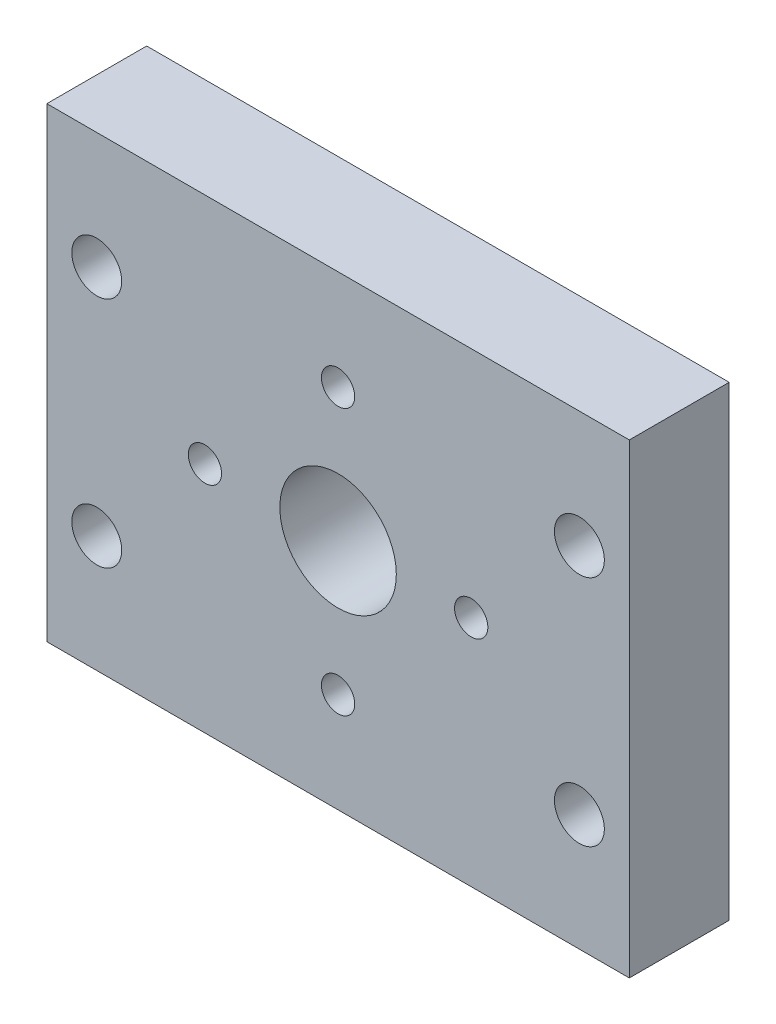
SolidWorks part; units mm, degrees
ref_plane "Plan de face" through (0, 0, 0) normal (0, 0, 1) x (1, 0, 0)
ref_plane "Plan de dessus" through (0, 0, 0) normal (0, 1, 0) x (1, 0, 0)
ref_plane "Plan de droite" through (0, 0, 0) normal (1, 0, 0) x (0, 0, -1)
sketch "Esquisse1" plane through (0, 0, 0) normal (0, 0, 1) x (1, 0, 0)
  line L0 (0, 0) -> (44.4207, 0) construction
  line L1 (17.5, -14) -> (-17.5, -14)
  line L2 (17.5, -14) -> (17.5, 14)
  line L3 (17.5, 14) -> (-17.5, 14)
  line L4 (-17.5, -14) -> (-17.5, 14)
  line L5 (17.5, -14) -> (-17.5, 14) construction
  line L6 (17.5, 14) -> (-17.5, -14) construction
  line L7 (0, 0) -> (0, -37.0394) construction
  line L8 (-11.5, 15) -> (-11.5, -24.3494) construction
  line L10 (-17.5, 14) -> (-11.5, 0) construction
  circle A0 centre (0, 0) radius 3.5
  circle A1 centre (0, 8) radius 1
  circle A2 centre (8, 0) radius 1
  circle A3 centre (0, -8) radius 1
  circle A4 centre (-8, 0) radius 1
  circle A5 centre (-14.5, 7) radius 1.5
  circle A6 centre (-14.5, -7) radius 1.5
  circle A7 centre (14.5, -7) radius 1.5
  circle A8 centre (14.5, 7) radius 1.5
  point P0 (0, 0)
  dimension "D1" = 7
  dimension "D2" = 2
  dimension "D3" = 2
  dimension "D4" = 2
  dimension "D5" = 2
  dimension "D7" = 8
  dimension "D12" = 3
  dimension "D6" = 8
  dimension "D8" = 8
  dimension "D9" = 8
  dimension "D10" = 35
  dimension "D11" = 28
  dimension "D15" = 3
extrude "Boss.-Extru.1" add sketch "Esquisse1" along normal blind 6 contours L4 L3 L2 L1 | A0 | A1 | A4 | A3 | A2 | A5 | A7 | A6 | A8
sketch "Esquisse2" plane through (0, 0, 6) normal (0, 0, 1) x (1, 0, 0)
  line L0 (17.5, 14) -> (-17.5, 14) construction
  line L1 (17.5, -14) -> (11.5, -14)
  line L2 (17.5, -14) -> (17.5, 14)
  line L3 (17.5, 14) -> (11.5, 14)
  line L4 (11.5, -14) -> (11.5, 14)
sketch "Esquisse5" plane through (0, 0, 6) normal (0, 0, 1) x (1, 0, 0)
  line L0 (17.5, 14) -> (-17.5, 14) construction
  line L1 (-17.5, -14) -> (-11.5, -14)
  line L2 (-17.5, -14) -> (-17.5, 14)
  line L3 (-17.5, 14) -> (-11.5, 14)
  line L4 (-11.5, -14) -> (-11.5, 14)
